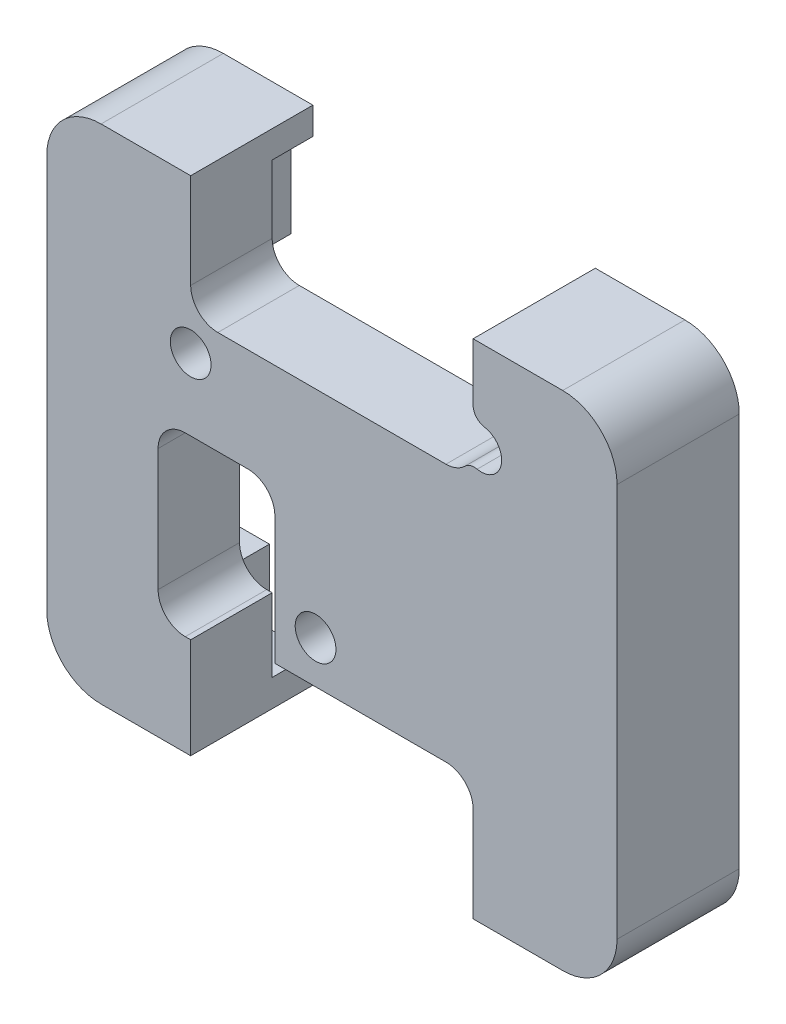
SolidWorks part; units mm, degrees
ref_plane "Top Plane" through (0, 0, 0) normal (0, 0, 1) x (1, 0, 0)
ref_plane "Right Plane" through (0, 0, 0) normal (0, 1, 0) x (1, 0, 0)
ref_plane "Front Plane" through (0, 0, 0) normal (1, 0, 0) x (0, 0, -1)
sketch "Sketch1" plane through (0, 0, 0) normal (0, 0, 1) x (1, 0, 0)
  line L1 (2, 0) -> (5.3, 0)
  line L2 (0, 2) -> (0, 16.5)
  line L3 (2, 18.5) -> (5.3, 18.5)
  line L4 (21, 2) -> (21, 16.5)
  line L5 (20, 2) -> (20, 16.5) construction
  line L6 (1, 3.7) -> (1, 14)
  line L7 (4.5, 17.5) -> (5.3, 17.5)
  line L8 (20, 2) -> (20, 14)
  line L9 (3.7, 1) -> (5.3, 1)
  line L10 (5.3, 0) -> (5.3, 1)
  line L11 (5.3, 17.5) -> (5.3, 18.5)
  line L12 (15.7, 0) -> (15.7, 1)
  line L13 (16.5, 17.5) -> (16.5, 14)
  line L14 (15.7, 17.5) -> (15.7, 18.5)
  line L15 (16.5, 14) -> (20, 14)
  line L16 (1, 3.7) -> (3.7, 3.7)
  line L17 (3.7, 3.7) -> (3.7, 1)
  line L18 (1, 14) -> (4.5, 14)
  line L19 (4.5, 14) -> (4.5, 17.5)
  line L20 (15.7, 18.5) -> (19, 18.5)
  line L21 (15.7, 17.5) -> (16.5, 17.5)
  line L22 (5.3, 18.5) -> (15.7, 18.5) construction
  line L23 (2, 18.5) -> (19, 18.5) construction
  line L24 (15.7, 1) -> (19, 1)
  line L25 (5.3, 17.5) -> (15.7, 17.5) construction
  line L26 (2, 17.5) -> (19, 17.5) construction
  line L27 (15.7, 0) -> (19, 0)
  line L28 (5.3, 1) -> (15.7, 1) construction
  line L29 (2, 1) -> (19, 1) construction
  line L31 (5.3, 0) -> (15.7, 0) construction
  line L32 (2, 0) -> (19, 0) construction
  line L33 (1, 2) -> (1, 16.5) construction
  arc A0 (2, 0) -> (0, 2) centre (2, 2) cw
  arc A1 (19, 0) -> (21, 2) centre (19, 2) ccw
  arc A2 (19, 18.5) -> (21, 16.5) centre (19, 16.5) cw
  arc A3 (0, 16.5) -> (2, 18.5) centre (2, 16.5) cw
  arc A6 (19, 1) -> (20, 2) centre (19, 2) ccw
  arc A9 (2, 1) -> (1, 2) centre (2, 2) cw construction
  arc A10 (19, 17.5) -> (20, 16.5) centre (19, 16.5) cw construction
  arc A11 (1, 16.5) -> (2, 17.5) centre (2, 16.5) cw construction
  point P7 (0, 0)
  point P10 (21, 0)
  point P15 (0, 18.5)
  dimension "D3" = 2
  dimension "D6" = 3.5
  dimension "D1" = 18.5
  dimension "D2" = 21
  dimension "D5" = 2.7
  dimension "D7" = 10.4
  dimension "D4" = 1
extrude "Boss-Extrude1" add sketch "Sketch1" along normal blind 1.5
sketch "Sketch2" plane through (0, 0, 1.5) normal (0, 0, 1) x (1, 0, 0)
  line L0 (19, 18.5) -> (15.7, 18.5) construction
  line L1 (21, 2) -> (21, 16.5) construction
  line L2 (15.7, 0) -> (19, 0) construction
  line L3 (2, 0) -> (5.3, 0) construction
  line L4 (0, 16.5) -> (0, 2) construction
  line L5 (5.3, 18.5) -> (2, 18.5) construction
  line L6 (19, 18.5) -> (15.7, 18.5)
  line L7 (21, 2) -> (21, 16.5)
  line L8 (15.7, 0) -> (19, 0)
  line L9 (2, 0) -> (5.3, 0)
  line L10 (0, 16.5) -> (0, 2)
  line L11 (5.3, 18.5) -> (2, 18.5)
  line L12 (5.3, 18.5) -> (5.3, 14)
  line L13 (5.3, 14) -> (15.7, 14)
  line L14 (15.7, 14) -> (15.7, 18.5)
  line L15 (5.3, 0) -> (5.3, 3.7)
  line L16 (5.3, 3.7) -> (4.1, 3.7)
  line L17 (4.1, 3.7) -> (4.1, 10.2)
  line L18 (4.1, 10.2) -> (8.4, 10.2)
  line L19 (8.4, 10.2) -> (8.4, 4.5)
  line L20 (8.4, 4.5) -> (15.7, 4.5)
  line L21 (15.7, 4.5) -> (15.7, 0)
  line L22 (3.7, 3.7) -> (1, 3.7) construction
  line L24 (1, 14) -> (4.5, 14) construction
  arc A0 (21, 16.5) -> (19, 18.5) centre (19, 16.5) ccw construction
  arc A1 (19, 0) -> (21, 2) centre (19, 2) ccw construction
  arc A2 (0, 2) -> (2, 0) centre (2, 2) ccw construction
  arc A3 (2, 18.5) -> (0, 16.5) centre (2, 16.5) ccw construction
  arc A4 (21, 16.5) -> (19, 18.5) centre (19, 16.5) ccw
  arc A5 (19, 0) -> (21, 2) centre (19, 2) ccw
  arc A6 (0, 2) -> (2, 0) centre (2, 2) ccw
  arc A7 (2, 18.5) -> (0, 16.5) centre (2, 16.5) ccw
  dimension "D1" = 4.3
  dimension "D2" = 1.2
  dimension "D3" = 6.5
extrude "Boss-Extrude2" add sketch "Sketch2" along normal blind 3
fillet "Fillet1" radius 1 6 edges at (5.3, 14, 3) (15.7, 14, 3) (15.7, 4.5, 3) (8.4, 10.2, 3) (4.1, 10.2, 3) (4.1, 3.7, 3)
sketch "Sketch3" plane through (0, 0, 4.5) normal (0, 0, 1) x (1, 0, 0)
  circle A0 centre (9.8986, 6.0657) radius 0.75
  circle A1 centre (5.3005, 12.837) radius 0.75
  circle A2 centre (16, 15.15) radius 0.75
  point P6 (0, 0)
  point P7 (5.5, 13.183)
  point P8 (16, 15.15)
  point P10 (5.5, 13.05)
  point P12 (9.4, 5.91)
  point P14 (0, 0)
  point P15 (5.3005, 12.837)
  point P16 (9.8986, 6.0657)
  dimension "D1" = 1.5
extrude "Cut-Extrude2" cut sketch "Sketch3" against normal through all
fillet "Fillet2" radius 0.5 2 edges at (15.5814, 14.5277, 3) (15.7, 15.8374, 3)
